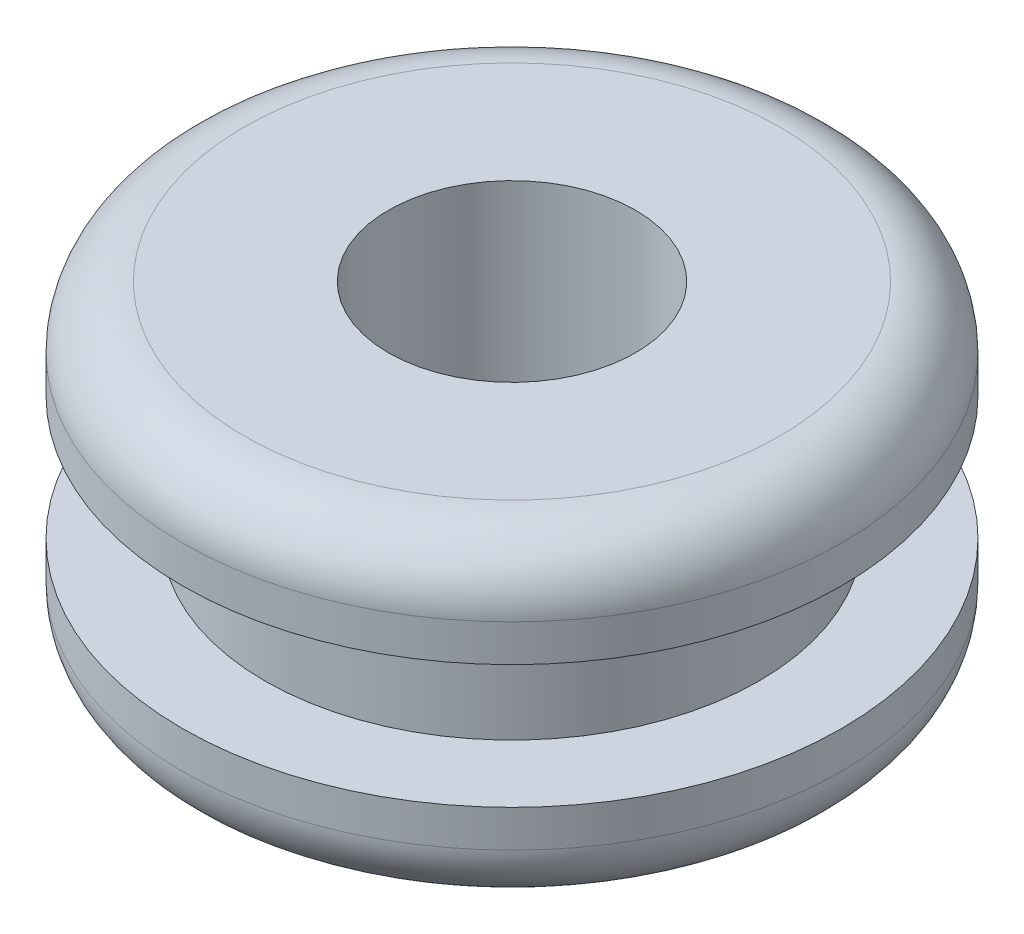
SolidWorks part; units mm, degrees
ref_plane "Front Plane" through (0, 0, 0) normal (0, 0, 1) x (1, 0, 0)
ref_plane "Top Plane" through (0, 0, 0) normal (0, 1, 0) x (1, 0, 0)
ref_plane "Right Plane" through (0, 0, 0) normal (1, 0, 0) x (0, 0, -1)
sketch "Sketch1" plane through (0, 0, 0) normal (1, 0, 0) x (0, 0, -1)
  line L0 (0, 0) -> (0, 1.95) construction
  line L1 (0, 0) -> (-1.5, 0) construction
  line L2 (-1.5, -1.95) -> (-1.5, 1.95)
  line L3 (-3, -0.75) -> (-3, 0.75)
  line L4 (-3, 0.75) -> (-4, 0.75)
  line L5 (-1.5, 1.95) -> (-3.25, 1.95)
  line L6 (-4, 0.75) -> (-4, 1.2)
  line L7 (-1.5, -1.95) -> (-3.25, -1.95)
  line L8 (-4, -0.75) -> (-4, -1.2)
  line L9 (-3, -0.75) -> (-4, -0.75)
  arc A0 (-4, 1.2) -> (-3.25, 1.95) centre (-3.25, 1.2) cw
  arc A1 (-4, -1.2) -> (-3.25, -1.95) centre (-3.25, -1.2) ccw
  point P11 (-3.3621, 1.3121)
  point P12 (0, 0)
  point P19 (-3, 0)
  dimension "D6" = 6
  dimension "D5" = 0.75
  dimension "D1" = 3
  dimension "D2" = 3.9
  dimension "D3" = 8
  dimension "D4" = 1.5
revolve "Revolve1" add sketch "Sketch1" angle 360 about L0
